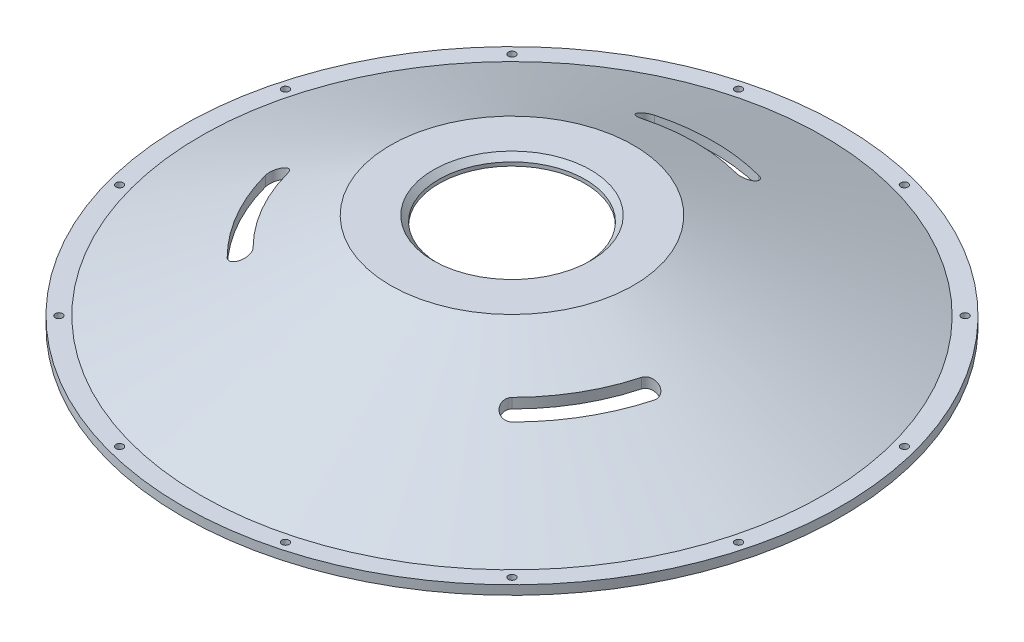
SolidWorks part; units mm, degrees
ref_plane "前视基准面" through (0, 0, 0) normal (0, 0, 1) x (1, 0, 0)
ref_plane "上视基准面" through (0, 0, 0) normal (0, 1, 0) x (1, 0, 0)
ref_plane "右视基准面" through (0, 0, 0) normal (1, 0, 0) x (0, 0, -1)
sketch "草图1" plane through (0, 0, 0) normal (0, 1, 0) x (1, 0, 0)
  circle A0 centre (0, 0) radius 50
  circle A1 centre (0, 0) radius 60
  dimension "D1" = 100
  dimension "D2" = 120
extrude "凸台-拉伸1" add sketch "草图1" along normal blind 5
sketch "草图2" plane through (0, 5, 0) normal (0, 1, 0) x (1, 0, 0)
  circle A0 centre (0, 0) radius 53.5347
  circle A1 centre (0, 0) radius 39.9719
extrude "凸台-拉伸2" add sketch "草图2" against normal blind 5
chamfer "倒角1" distance 3 angle 45 1 edges at (0, 5, 39.9719)
sketch "草图4" plane through (0, 0, 0) normal (0, 0, 1) x (1, 0, 0)
  line L0 (0, 90.9424) -> (0, -193.821) construction
  line L1 (-50.3647, 0) -> (-65.2735, 0)
  line L2 (62.5, 0) -> (-62.5, 0) construction
  line L3 (-50.3647, 5) -> (-66.3647, 5)
  line L4 (60, 5) -> (-60, 5) construction
  line L5 (-50.3647, 5) -> (-50.3647, 0)
  line L6 (-65.2735, 0) -> (-168.9087, -47.5)
  line L7 (-168.9087, -47.5) -> (-180, -47.5)
  line L8 (-180, -47.5) -> (-180, -42.5)
  line L9 (-180, -42.5) -> (-170, -42.5)
  line L10 (-170, -42.5) -> (-66.3647, 5)
  dimension "D1" = 5
  dimension "D2" = 5
  dimension "D3" = 180
  dimension "D4" = 16
  dimension "D5" = 10
revolve "旋转1" add sketch "草图4" angle 360 about L0
sketch "草图5" plane through (0, -42.5, 0) normal (0, 1, 0) x (1, 0, 0)
  line L0 (0, 203.5839) -> (0, -196.6191) construction
  circle A0 centre (0, 175) radius 2
  circle A1 centre (0, 0) radius 170 construction
  dimension "D1" = 4
  dimension "D2" = 175
extrude "切除-拉伸1" cut sketch "草图5" against normal blind 50
pattern_circular "阵列(圆周)1" count 8 over 360 about axis through (0, 0, 0) along (0, 1, 0) of "切除-拉伸1"
ref_plane "基准面1" through (0, -37.5, 0) normal (0, -1, 0) x (-1, 0, 0)
sketch "草图6" plane through (0, -37.5, 0) normal (0, -1, 0) x (-1, 0, 0)
  line L0 (-340.9647, 0) -> (294.745, 0) construction
  line L1 (0, 290.5777) -> (0, -327.9808) construction
  circle A0 centre (-110, 0) radius 3.4
  dimension "D1" = 6.8
  dimension "D2" = 110
extrude "配重柱子" add sketch "草图6" against normal up to next
pattern_circular "阵列(圆周)2" count 6 over 360 about axis through (0, 0, 0) along (0, 1, 0) of "配重柱子"
sketch "草图7" plane through (0, 5, 0) normal (0, 1, 0) x (1, 0, 0)
  line L5 (0, -100) -> (0, -110) construction
  arc A2 (25.8819, 96.5926) -> (-25.8819, 96.5926) centre (0, 0) ccw
  arc A3 (28.4701, 106.2518) -> (-28.4701, 106.2518) centre (0, 0) ccw
  arc A4 (-28.4701, 106.2518) -> (-25.8819, 96.5926) centre (-27.176, 101.4222) ccw
  arc A5 (25.8819, 96.5926) -> (28.4701, 106.2518) centre (27.176, 101.4222) ccw
extrude "切除-拉伸2" cut sketch "草图7" against normal blind 500
pattern_circular "阵列(圆周)3" count 3 over 360 about axis through (0, 0, 0) along (0, 1, 0) of "切除-拉伸2"
sketch "草图8" plane through (0, -42.5, 0) normal (0, 1, 0) x (1, 0, 0)
  circle A0 centre (-175, 0) radius 2
extrude "凸台-拉伸3" add sketch "草图8" against normal up to surface (5 mm away) up to face at (-175, -47.5, -2)
pattern_circular "阵列(圆周)4" count 4 over 360 about axis through (0, 90.9424, 0) along (0, 1, 0) of "凸台-拉伸3"
sketch "草图9" plane through (0, -42.5, 0) normal (0, 1, 0) x (1, 0, 0)
  line L0 (0, 0) -> (-123.7437, -123.7437) construction
  line L1 (0, 0) -> (123.7437, -123.7437) construction
  line L2 (0, 0) -> (123.7437, 123.7437) construction
  line L3 (-123.7437, 123.7437) -> (0, 0) construction
  line L4 (0, 0) -> (-169.037, 45.2933) construction
  line L5 (0, 0) -> (-169.037, -45.2933) construction
  circle A0 centre (-169.037, 45.2933) radius 2
  circle A1 centre (-169.037, -45.2933) radius 2
  dimension "D5" = 4
  dimension "D1" = 30
  dimension "D2" = 30
  dimension "D3" = 175
  dimension "D4" = 175
extrude "切除-拉伸3" cut sketch "草图9" against normal blind 50
pattern_circular "阵列(圆周)5" count 4 over 360 about axis through (0, 0, 0) along (0, 1, 0) of "切除-拉伸3"
sketch "草图13" plane through (0, -37.5, 0) normal (0, -1, 0) x (1, 0, 0)
  circle A0 centre (-55, -95.2628) radius 1.5
  circle A1 centre (0, 0) radius 1.6031
  circle A2 centre (-55, -95.2628) radius 3.4 construction
  dimension "D1" = 3
extrude "切除-拉伸4" cut sketch "草图13" against normal blind 3
pattern_circular "阵列(圆周)6" count 6 over 360 about axis through (0, 0, 0) along (0, 1, 0) of "切除-拉伸4"
